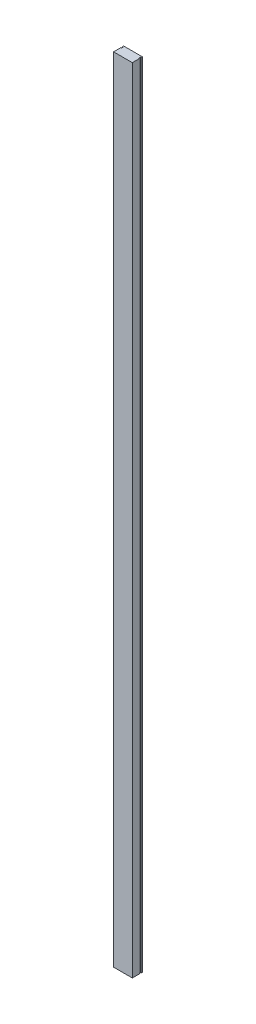
SolidWorks part; units mm, degrees
ref_plane "前基準面" through (0, 0, 0) normal (0, 0, 1) x (1, 0, 0)
ref_plane "上基準面" through (0, 0, 0) normal (0, 1, 0) x (1, 0, 0)
ref_plane "右基準面" through (0, 0, 0) normal (1, 0, 0) x (0, 0, -1)
sketch "草圖1" plane through (0, 0, 0) normal (0, 1, 0) x (1, 0, 0)
  line L0 (0, 0) -> (0, 16.1405) construction
  line L1 (-6.5, 0) -> (6.5, 0)
  line L2 (6.5, 0) -> (6.5, 5)
  line L3 (6.5, 5) -> (6, 5)
  line L4 (6, 5) -> (6, 6)
  line L5 (6, 6) -> (6.5, 6)
  line L6 (6.5, 6) -> (6.5, 7)
  line L7 (6.5, 7) -> (-6.5, 7)
  line L8 (-6.5, 6) -> (-6.5, 7)
  line L9 (-6, 6) -> (-6.5, 6)
  line L10 (-6, 5) -> (-6, 6)
  line L11 (-6.5, 5) -> (-6, 5)
  line L12 (-6.5, 0) -> (-6.5, 5)
  point P11 (0, 7)
  dimension "D1" = 7
  dimension "D2" = 1
  dimension "D3" = 1
  dimension "D4" = 0.5
  dimension "D5" = 13
extrude "填料-伸長1" add sketch "草圖1" along normal blind 550
sketch "草圖3" plane through (0, 0, -7) normal (0, 0, -1) x (-1, 0, 0)
  line L0 (0, 550) -> (0, 530.4017) construction
  line L1 (-6.5, 550) -> (6.5, 550) construction
  circle A0 centre (0, 540) radius 3
  dimension "D1" = 6
  dimension "D2" = 10
extrude "除料-伸長2" cut sketch "草圖3" against normal blind 5
sketch "草圖4" plane through (0, 0, -2) normal (0, 0, -1) x (-1, 0, 0)
  line L1 (1.7321, 540) -> (0.866, 541.5)
  line L2 (0.866, 541.5) -> (-0.866, 541.5)
  line L3 (-0.866, 541.5) -> (-1.7321, 540)
  line L4 (-1.7321, 540) -> (-0.866, 538.5)
  line L5 (-0.866, 538.5) -> (0.866, 538.5)
  line L6 (0.866, 538.5) -> (1.7321, 540)
  circle A0 centre (0, 540) radius 2.5
  circle A1 centre (0, 540) radius 1.5 construction
  dimension "D1" = 5
  dimension "D2" = 3
extrude "填料-伸長2" add sketch "草圖4" along normal blind 3
pattern_linear "直線複製排列1" count 9 spacing 63 along (0, -1, 0) of "填料-伸長2", "除料-伸長2"
